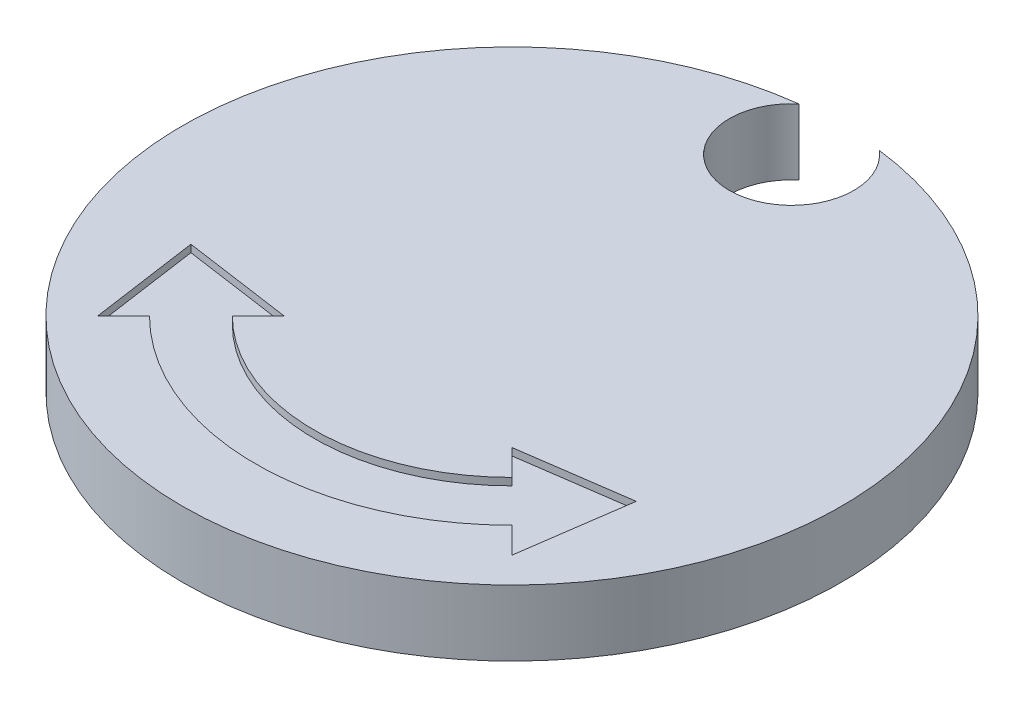
SolidWorks part; units mm, degrees
material "ABS"
ref_plane "Front Plane" through (0, 0, 0) normal (0, 0, 1) x (1, 0, 0)
ref_plane "Top Plane" through (0, 0, 0) normal (0, 1, 0) x (1, 0, 0)
ref_plane "Right Plane" through (0, 0, 0) normal (1, 0, 0) x (0, 0, -1)
sketch "Sketch1" plane through (0, 0, 0) normal (0, 1, 0) x (1, 0, 0)
  circle A0 centre (0, 0) radius 45
  dimension "D1" = 90
extrude "Boss-Extrude1" add sketch "Sketch1" along normal blind 9
sketch "Sketch3" plane through (0, 9, 0) normal (0, 1, 0) x (1, 0, 0)
  line L0 (0, -4.95) -> (0, 4.95) construction
  line L1 (5.5, 44.6626) -> (-5.5, 44.6626) construction
  circle A0 centre (0, 38.1819) radius 8.5
  circle A1 centre (0, 0) radius 45 construction
  point P10 (0, 44.6626)
  dimension "D1" = 17
  dimension "D2" = 11
extrude "Cut-Extrude2" cut sketch "Sketch3" against normal blind 10 contours A0
sketch "Sketch4" plane through (0, 0, 0) normal (0, -1, 0) x (1, 0, 0)
  circle A0 centre (0, 0) radius 3
  dimension "D1" = 6
extrude "Boss-Extrude2" add sketch "Sketch4" along normal blind 6
sketch "Sketch5" plane through (0, -6, 0) normal (0, -1, 0) x (1, 0, 0)
  circle A0 centre (0, 0) radius 2.5
  dimension "D1" = 5
extrude "Cut-Extrude3" cut sketch "Sketch5" against normal blind 5
sketch "Sketch6" plane through (0, 9, 0) normal (0, 1, 0) x (1, 0, 0)
  line L0 (-24.7487, -24.7487) -> (-28.2843, -28.2843)
  line L1 (-28.2843, -28.2843) -> (-30.4056, -13.435)
  line L2 (-30.4056, -13.435) -> (-15.5563, -15.5563)
  line L3 (-15.5563, -15.5563) -> (-19.0919, -19.0919)
  line L4 (19.0919, -19.0919) -> (15.5563, -15.5564)
  line L5 (15.5563, -15.5564) -> (30.4056, -13.435)
  line L6 (30.4056, -13.435) -> (28.2843, -28.2843)
  line L7 (28.2843, -28.2843) -> (24.7487, -24.7487)
  line L8 (0, 0) -> (0, -45) construction
  arc A0 (-19.0919, -19.0919) -> (19.0919, -19.0919) centre (0, 0) ccw
  arc A1 (-24.7487, -24.7487) -> (24.7487, -24.7487) centre (0, 0) ccw
  arc A2 (-15.5563, -15.5563) -> (15.5563, -15.5564) centre (0, 0) ccw construction
  arc A3 (-5.5, 44.6626) -> (5.5, 44.6626) centre (0, 0) ccw construction
  point P11 (26.5227, -26.5227)
  point P13 (20.8659, -20.8659)
  point P18 (17.3303, -17.3303)
  point P19 (30.4056, -13.435)
  point P20 (15.5564, -15.5563)
  point P21 (19.0919, -19.0919)
  point P22 (24.7487, -24.7487)
  point P23 (0, 0)
  point P24 (28.283, -28.2843)
  point P25 (19.0919, -19.0919)
  point P26 (30.4056, -13.435)
  point P27 (24.7487, -24.7487)
  point P28 (28.2843, -28.2843)
  point P29 (15.5563, -15.5563)
  point P30 (19.0919, -19.0919)
  point P31 (30.4056, -13.435)
  dimension "D3" = 8
  dimension "D1" = 45
  dimension "D2" = 45
  dimension "D4" = 5
  dimension "D5" = 15
  dimension "D6" = 40
extrude "Cut-Extrude4" cut sketch "Sketch6" against normal blind 1
